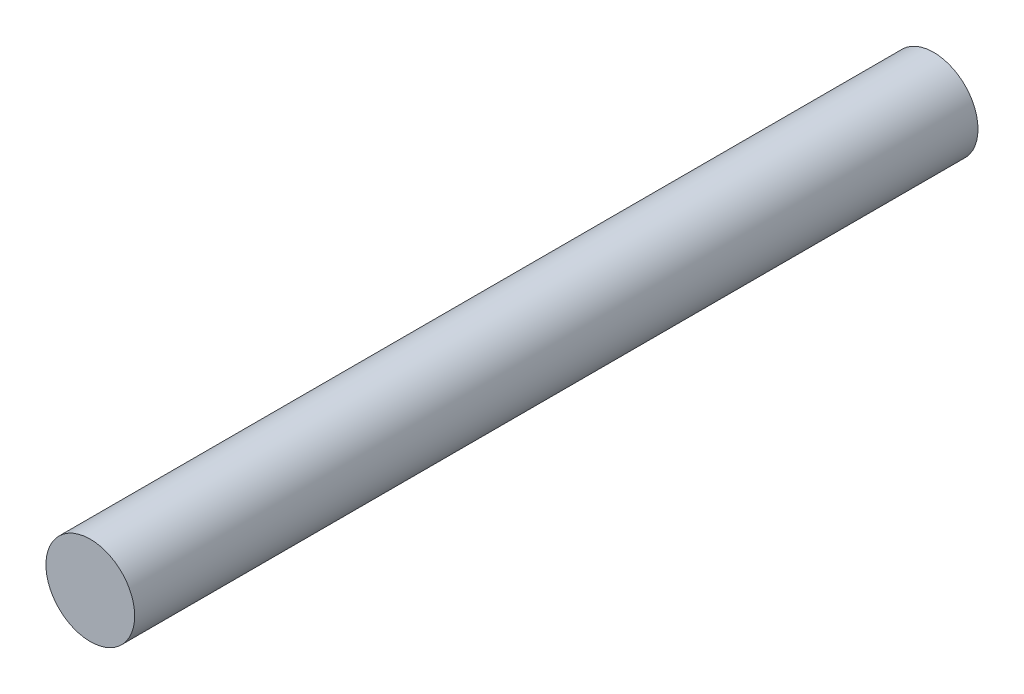
SolidWorks part; units mm, degrees
ref_plane "Front" through (0, 0, 0) normal (0, 0, 1) x (1, 0, 0)
ref_plane "Top" through (0, 0, 0) normal (0, 1, 0) x (1, 0, 0)
ref_plane "Right" through (0, 0, 0) normal (1, 0, 0) x (0, 0, -1)
sketch "Sketch1" plane through (0, 0, 0) normal (0, 0, 1) x (1, 0, 0)
  circle A0 centre (0, 0) radius 4
  dimension "D1" = 8
extrude "Boss-Extrude1" add sketch "Sketch1" along normal blind 76
equation "\"xplate-supporttab-gapwidth\"= 40mm"
equation "\"material-thickness\"= 9mm"
equation "\"D1@Boss-Extrude1\"=\"xplate-supporttab-gapwidth\"+(\"material-thickness\"*4)"
equation "\"linear-xbar-dia\"= 8mm ' Diameter of the metal slide bar used on the X Axis"
equation "\"D1@Sketch1\"=\"linear-xbar-dia\""
